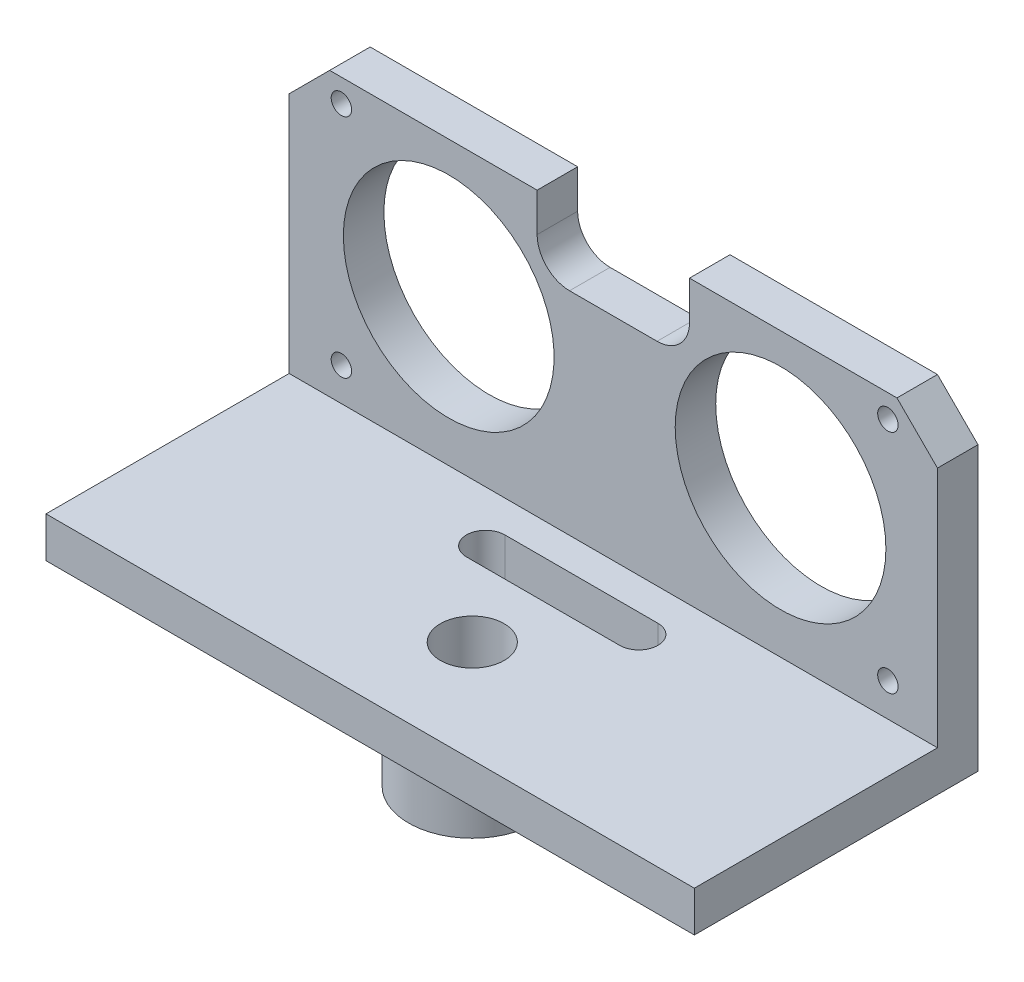
SolidWorks part; units mm, degrees
ref_plane "Front Plane" through (0, 0, 0) normal (0, 0, 1) x (1, 0, 0)
ref_plane "Top Plane" through (0, 0, 0) normal (0, 1, 0) x (1, 0, 0)
ref_plane "Right Plane" through (0, 0, 0) normal (1, 0, 0) x (0, 0, -1)
sketch "Sketch1" plane through (0, 0, 0) normal (0, 0, 1) x (1, 0, 0)
  line L1 (-25.4, 17.018) -> (25.4, 17.018)
  line L2 (-25.4, 17.018) -> (-25.4, -17.018)
  line L3 (-25.4, -17.018) -> (25.4, -17.018)
  line L4 (25.4, 17.018) -> (25.4, -17.018)
  line L5 (-25.4, 17.018) -> (25.4, -17.018) construction
  line L6 (-25.4, -17.018) -> (25.4, 17.018) construction
  point P0 (0, 0)
  dimension "D1" = 50.8
  dimension "D2" = 34.036
extrude "Boss-Extrude1" add sketch "Sketch1" along normal mid plane 3.175
chamfer "Chamfer2" distance 3.175 angle 45 2 edges at (25.4, 17.018, 0) (-25.4, 17.018, 0)
sketch "Sketch5" plane through (0, 0, -1.5875) normal (0, 0, -1) x (-1, 0, 0)
  line L0 (-5.969, 14.0011) -> (-5.969, 17.018)
  line L1 (-22.225, 17.018) -> (22.225, 17.018) construction
  line L2 (5.969, 14.0011) -> (5.969, 17.018)
  line L3 (-3.429, 11.4611) -> (3.429, 11.4611)
  line L4 (-25.4, -17.018) -> (-25.4, 13.843) construction
  line L5 (-5.969, 17.018) -> (5.969, 17.018)
  arc A0 (5.969, 14.0011) -> (3.429, 11.4611) centre (3.429, 14.0011) cw
  arc A1 (-3.429, 11.4611) -> (-5.969, 14.0011) centre (-3.429, 14.0011) cw
  dimension "D2" = 2.54
  dimension "D4" = 19.431
  dimension "D1" = 11.938
  dimension "D3" = 5.5569
extrude "Cut-Extrude1" cut sketch "Sketch5" against normal up to surface (3.175 mm away) up to face at (0, 4.6143, 1.5875)
sketch "Sketch7" plane through (0, 0, -1.5875) normal (0, 0, -1) x (-1, 0, 0)
  circle A0 centre (12.896, 6.34) radius 8.255
  dimension "D1" = 16.51
extrude "Cut-Extrude3" cut sketch "Sketch7" against normal up to surface (3.175 mm away) up to face at (0, 9.2995, 1.5875)
sketch "Sketch8" plane through (0, 0, -1.5875) normal (0, 0, -1) x (-1, 0, 0)
  circle A0 centre (-13.104, 6.34) radius 8.255
  dimension "D1" = 16.51
extrude "Cut-Extrude4" cut sketch "Sketch8" against normal up to surface (3.175 mm away) up to face at (-4.641, 6.34, 1.5875)
sketch "Sketch9" plane through (0, 0, 1.5875) normal (0, 0, 1) x (1, 0, 0)
  circle A0 centre (-21.306, 15.21) radius 0.8
  circle A1 centre (21.514, 15.21) radius 0.8
  circle A2 centre (21.514, -2.53) radius 0.8
  circle A3 centre (-21.306, -2.53) radius 0.8
extrude "Cut-Extrude5" cut sketch "Sketch9" against normal up to surface (3.175 mm away) up to face at (4.849, 6.34, -1.5875)
sketch "草图1" plane through (0, 0, 1.5875) normal (0, 0, 1) x (1, 0, 0)
  line L0 (-25.4, -8.318) -> (25.4, -8.318)
  line L1 (-25.4, 13.843) -> (-25.4, -17.018) construction
  line L2 (25.4, -17.018) -> (25.4, 13.843) construction
  line L3 (-25.4, -17.018) -> (25.4, -17.018) construction
  line L4 (-25.4, -8.318) -> (-25.4, -17.018)
  line L5 (-25.4, -17.018) -> (25.4, -17.018)
  line L6 (25.4, -17.018) -> (25.4, -8.318)
  dimension "D1" = 8.7
extrude "切除-拉伸1" cut sketch "草图1" against normal blind 10
sketch "草图2" plane through (0, 0, 1.5875) normal (0, 0, 1) x (1, 0, 0)
  line L0 (-25.4, -8.318) -> (-25.4, -5.138)
  line L2 (-25.4, 13.843) -> (-25.4, -8.318) construction
  line L3 (-25.4, -5.138) -> (25.4, -5.138)
  line L4 (25.4, -8.318) -> (25.4, 13.843) construction
  line L5 (25.4, -5.138) -> (25.4, -8.318)
  line L6 (25.4, -8.318) -> (-25.4, -8.318)
  dimension "D1" = 3.18
extrude "凸台-拉伸1" add sketch "草图2" along normal blind 19.05
sketch "草图3" plane through (0, -5.138, 0) normal (0, 1, 0) x (1, 0, 0)
  line L0 (0, 6.2968) -> (0, -24.3755) construction
  line L1 (25.4, -20.6375) -> (-25.4, -20.6375) construction
  circle A0 centre (0, -12.6375) radius 2.5
  dimension "D1" = 5
  dimension "D2" = 8
sketch "草图4" plane through (0, -5.138, 0) normal (0, 1, 0) x (1, 0, 0)
  line L0 (-6, -5.5875) -> (6, -5.5875) construction
  line L1 (-6, -4.0875) -> (6, -4.0875)
  line L2 (-6, -7.0875) -> (6, -7.0875)
  line L4 (0, 6.2968) -> (0, -24.3755) construction
  line L6 (3.429, -1.5875) -> (-3.429, -1.5875) construction
  arc A0 (-6, -4.0875) -> (-6, -7.0875) centre (-6, -5.5875) ccw
  arc A1 (6, -7.0875) -> (6, -4.0875) centre (6, -5.5875) ccw
  point P2 (0, -5.5875)
  dimension "D2" = 1.5
  dimension "D1" = 12
  dimension "D3" = 4
extrude "切除-拉伸2" cut sketch "草图4" against normal blind 10
extrude "切除-拉伸3" cut sketch "草图3" against normal blind 10 contours A0
sketch "草图5" plane through (0, -8.318, 0) normal (0, -1, 0) x (1, 0, 0)
  line L4 (25.4, -1.5875) -> (25.4, 20.6375)
  line L5 (25.4, 20.6375) -> (-25.4, 20.6375)
  line L6 (-25.4, 20.6375) -> (-25.4, -1.5875)
  line L7 (-25.4, -1.5875) -> (25.4, -1.5875)
  line L8 (25.4, -1.5875) -> (25.4, 20.6375)
  line L9 (25.4, 20.6375) -> (-25.4, 20.6375)
  line L10 (-25.4, 20.6375) -> (-25.4, -1.5875)
  line L11 (-25.4, -1.5875) -> (25.4, -1.5875)
  circle A0 centre (0, 12.6375) radius 5
  circle M5 centre (0, 12.6375) radius 2.5
  dimension "D2" = 10
  dimension "D1" = 0
extrude "凸台-拉伸2" add sketch "草图5" along normal blind 6.6 contours A0 M5
sketch "草图6" plane through (0, 0, 0) normal (0, 0, 1) x (1, 0, 0)
  line L4 (-25.4, -8.318) -> (25.4, -8.318)
  line L5 (25.4, -8.318) -> (25.4, -5.138)
  line L6 (25.4, -5.138) -> (-25.4, -5.138)
  line L7 (-25.4, -5.138) -> (-25.4, -8.318)
  line L8 (-25.4, -8.318) -> (25.4, -8.318)
  line L9 (25.4, -8.318) -> (25.4, -5.138)
  line L10 (25.4, -5.138) -> (-25.4, -5.138)
  line L11 (-25.4, -5.138) -> (-25.4, -8.318)
  circle A0 centre (0, -11.518) radius 1.6
  dimension "D2" = 3.2
  dimension "D3" = 3.2
  dimension "D4" = 25.4
  dimension "D1" = 0
extrude "切除-拉伸4" cut sketch "草图6" along normal up to next contours A0
fillet "圆角1" radius 1 1 edges at (0, -8.318, 7.6375)
